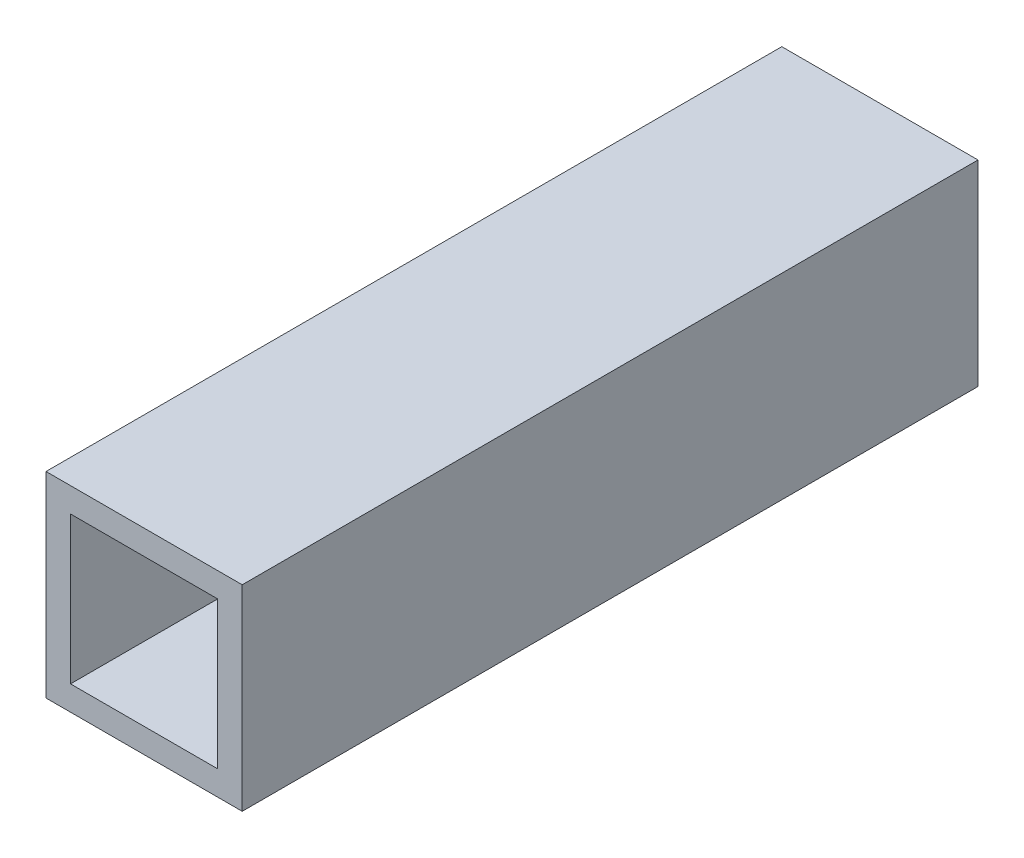
SolidWorks part; units mm, degrees
ref_plane "Front Plane" through (0, 0, 0) normal (0, 0, 1) x (1, 0, 0)
ref_plane "Top Plane" through (0, 0, 0) normal (0, 1, 0) x (1, 0, 0)
ref_plane "Right Plane" through (0, 0, 0) normal (1, 0, 0) x (0, 0, -1)
sketch "Sketch1" plane through (0, 0, 0) normal (0, 0, 1) x (1, 0, 0)
  line L1 (12.7, -12.7) -> (-12.7, -12.7)
  line L2 (12.7, -12.7) -> (12.7, 12.7)
  line L3 (12.7, 12.7) -> (-12.7, 12.7)
  line L4 (-12.7, -12.7) -> (-12.7, 12.7)
  line L5 (12.7, -12.7) -> (-12.7, 12.7) construction
  line L6 (12.7, 12.7) -> (-12.7, -12.7) construction
  line L7 (9.525, -9.525) -> (-9.525, -9.525)
  line L8 (9.525, -9.525) -> (9.525, 9.525)
  line L9 (9.525, 9.525) -> (-9.525, 9.525)
  line L10 (-9.525, -9.525) -> (-9.525, 9.525)
  line L11 (9.525, -9.525) -> (-9.525, 9.525) construction
  line L12 (9.525, 9.525) -> (-9.525, -9.525) construction
  point P0 (0, 0)
  point P6 (0, 0)
  dimension "D1" = 25.4
  dimension "D2" = 25.4
  dimension "D3" = 3.175
extrude "Boss-Extrude1" add sketch "Sketch1" along normal blind 95.25
